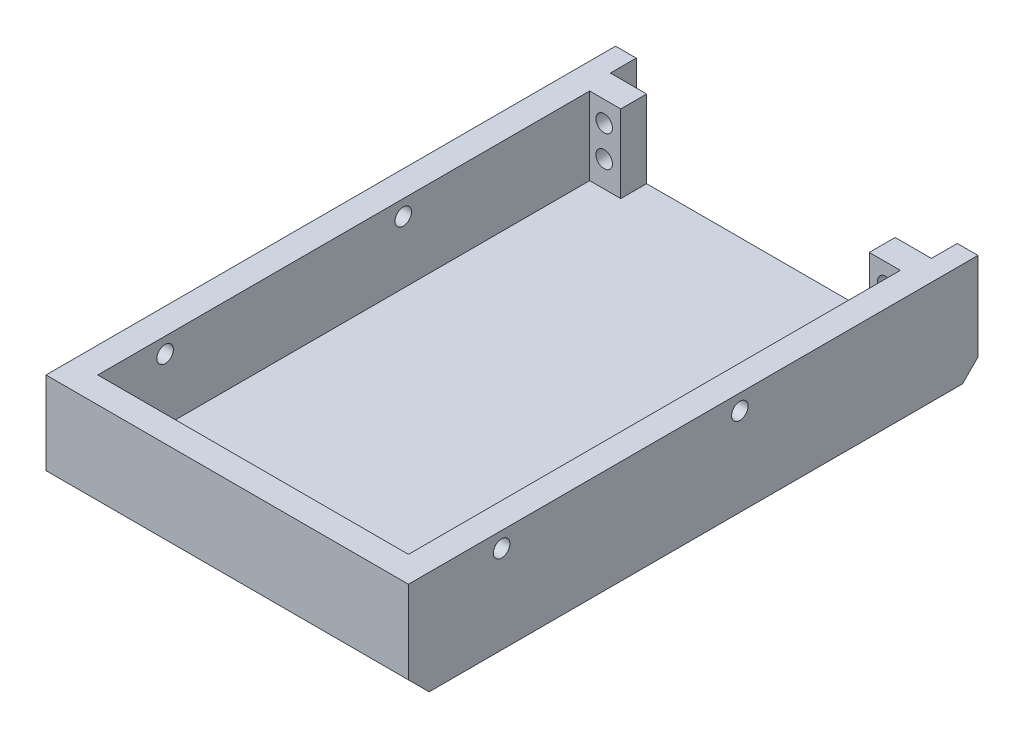
SolidWorks part; units mm, degrees
ref_plane "Alzado" through (0, 0, 0) normal (0, 0, 1) x (1, 0, 0)
ref_plane "Planta" through (0, 0, 0) normal (0, 1, 0) x (1, 0, 0)
ref_plane "Vista lateral" through (0, 0, 0) normal (1, 0, 0) x (0, 0, -1)
sketch "Croquis1" plane through (0, 0, 0) normal (0, 1, 0) x (1, 0, 0)
  line L1 (-35, -52.5) -> (35, -52.5)
  line L2 (-35, -52.5) -> (-35, 52.5)
  line L3 (-35, 52.5) -> (35, 52.5)
  line L4 (35, -52.5) -> (35, 52.5)
  line L5 (-35, -52.5) -> (35, 52.5) construction
  line L6 (-35, 52.5) -> (35, -52.5) construction
  point P0 (0, 0)
  dimension "D1" = 105
  dimension "D2" = 70
extrude "Saliente-Extruir1" add sketch "Croquis1" along normal blind 20
shell "Vaciado1" thickness 5
sketch "Croquis3" plane through (-35, 0, 0) normal (-1, 0, 0) x (0, 0, 1)
  line L0 (34.5, 17) -> (-11.5, 17) construction
  line L1 (52.5, 20) -> (52.5, 0) construction
  line L2 (-52.5, 20) -> (52.5, 20) construction
  circle A0 centre (34.5, 17) radius 1.6
  circle A1 centre (-11.5, 17) radius 1.6
  dimension "D1" = 3.2
  dimension "D2" = 3.2
  dimension "D3" = 46
  dimension "D4" = 18
  dimension "D5" = 3
extrude "Cortar-Extruir1" cut sketch "Croquis3" against normal blind 70
sketch "Croquis4" plane through (0, 0, -52.5) normal (0, 0, -1) x (-1, 0, 0)
  line L0 (-35, 20) -> (35, 20) construction
  line L1 (-30, 20) -> (30, 20)
  line L2 (-30, 20) -> (-30, 5)
  line L3 (-30, 5) -> (30, 5)
  line L4 (30, 20) -> (30, 5)
  line L5 (-35, 0) -> (35, 0) construction
  line L6 (35, 20) -> (35, 0) construction
  line L7 (-35, 20) -> (-35, 0) construction
  dimension "D1" = 5
  dimension "D2" = 5
  dimension "D3" = 5
extrude "Cortar-Extruir2" cut sketch "Croquis4" against normal blind 5
sketch "Croquis5" plane through (-30, 0, 0) normal (1, 0, 0) x (0, 0, -1)
  line L0 (-52.5, 20) -> (52.5, 20) construction
  line L1 (47.5, 20) -> (52.5, 20)
  line L2 (47.5, 20) -> (47.5, 5)
  line L3 (47.5, 5) -> (52.5, 5)
  line L4 (52.5, 20) -> (52.5, 5)
  dimension "D1" = 5
extrude "Saliente-Extruir2" add sketch "Croquis5" along normal blind 6
mirror "Simetría1" about plane through (0, 0, 0) normal (1, 0, 0) of "Saliente-Extruir2"
sketch "Croquis6" plane through (0, 0, -52.5) normal (0, 0, -1) x (-1, 0, 0)
  line L0 (-27.2, 16) -> (-27.2, 10) construction
  line L1 (-35, 20) -> (-24, 20) construction
  line L2 (-24, 5) -> (-24, 20) construction
  line L3 (-35, 20) -> (-35, 0) construction
  line L4 (-35, 0) -> (35, 0) construction
  circle A0 centre (-27.2, 16) radius 1.6
  circle A1 centre (-27.2, 10) radius 1.6
  dimension "D1" = 3.2
  dimension "D2" = 3.2
  dimension "D3" = 4
  dimension "D4" = 6
  dimension "D5" = 3.2
extrude "Cortar-Extruir3" cut sketch "Croquis6" against normal up to next
mirror "Simetría2" about plane through (0, 0, 0) normal (1, 0, 0) of "Cortar-Extruir3"
sketch "Croquis7" plane through (0, 0, 0) normal (0, 1, 0) x (1, 0, 0)
  line L0 (35, 57.5) -> (31, 57.5) construction
  line L1 (35, 57.5) -> (31, 57.5)
  line L2 (35, 57.5) -> (35, 52.5)
  line L3 (35, 52.5) -> (31, 52.5)
  line L4 (31, 57.5) -> (31, 52.5)
  dimension "D1" = 4
extrude "Saliente-Extruir3" add sketch "Croquis7" along normal up to surface (20 mm away) up to face at (0, 20, -16.6667)
chamfer "Chaflán1" distance 3 angle 45 1 edges at (33, 0, -57.5)
mirror "Simetría3" about plane through (0, 0, 0) normal (1, 0, 0) of "Chaflán1", "Saliente-Extruir3"
chamfer "Chaflán2" distance 4 angle 45 1 edges at (0, 0, 52.5)
